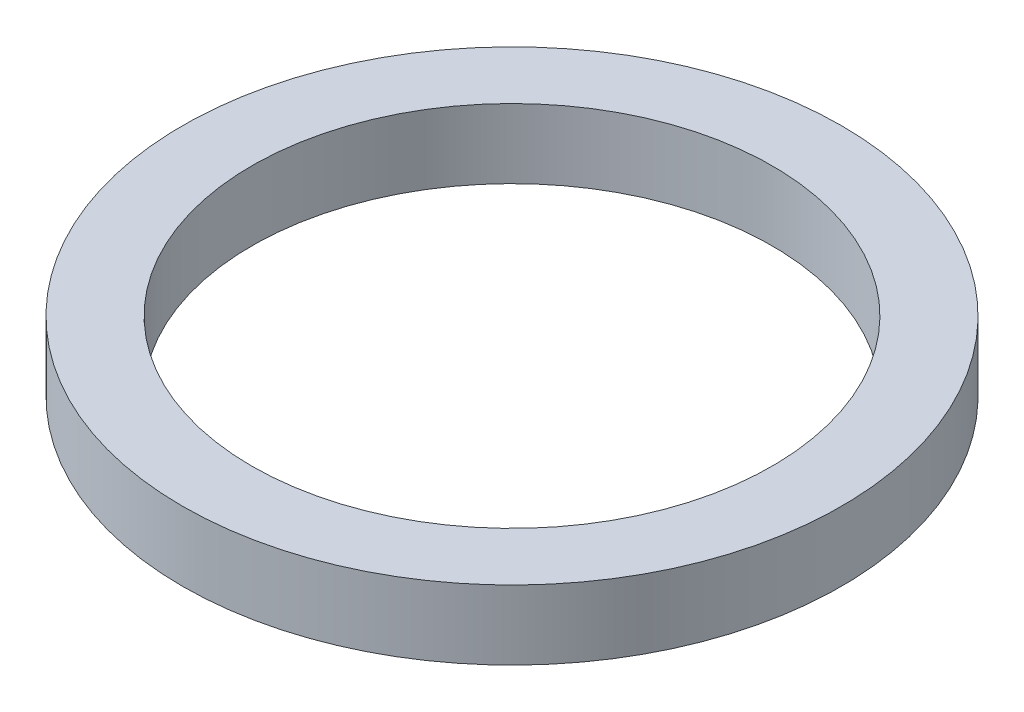
SolidWorks part; units mm, degrees
ref_plane "前视基准面" through (0, 0, 0) normal (0, 0, 1) x (1, 0, 0)
ref_plane "上视基准面" through (0, 0, 0) normal (0, 1, 0) x (1, 0, 0)
ref_plane "右视基准面" through (0, 0, 0) normal (1, 0, 0) x (0, 0, -1)
sketch "草图1" plane through (0, 0, 0) normal (0, 1, 0) x (1, 0, 0)
  circle A0 centre (0, 0) radius 47.5
  circle A1 centre (0, 0) radius 37.5
  dimension "D1" = 95
  dimension "D2" = 75
extrude "凸台-拉伸1" add sketch "草图1" along normal blind 10
